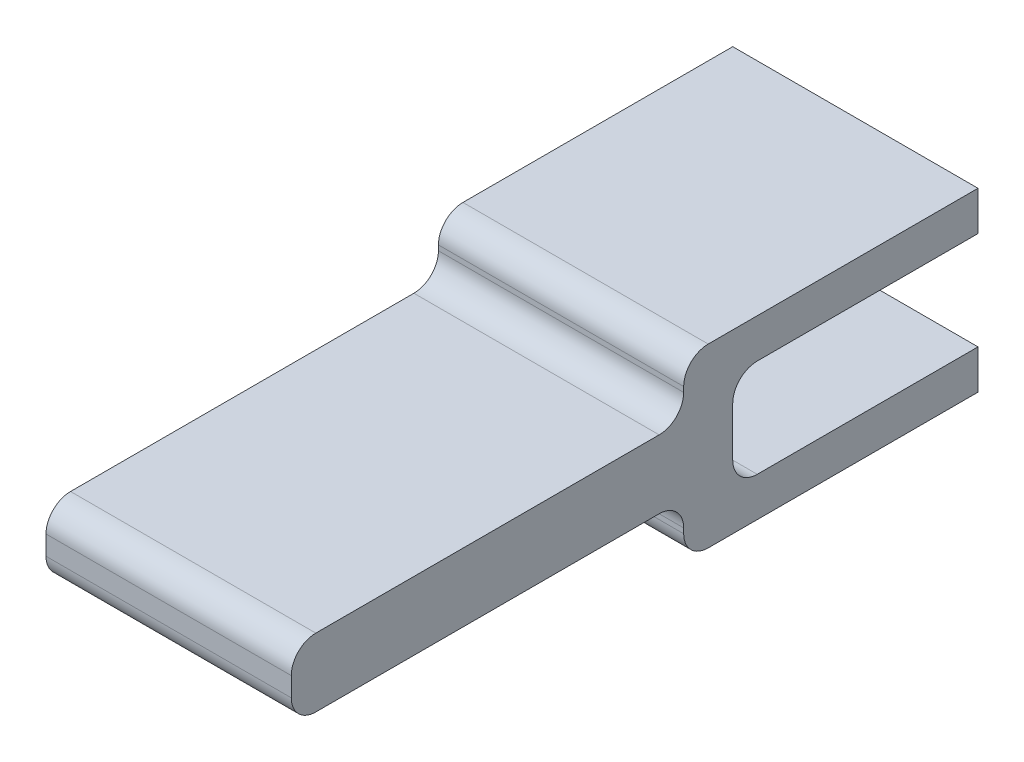
SolidWorks part; units mm, degrees
ref_plane "Front" through (0, 0, 0) normal (0, 0, 1) x (1, 0, 0)
ref_plane "Top" through (0, 0, 0) normal (0, 1, 0) x (1, 0, 0)
ref_plane "Right" through (0, 0, 0) normal (1, 0, 0) x (0, 0, -1)
sketch "Эскиз1" plane through (0, 0, 0) normal (0, 0, 1) x (1, 0, 0)
  line L1 (-2.5, 1) -> (2.5, 1)
  line L2 (-2.5, 1) -> (-2.5, -1)
  line L3 (-2.5, -1) -> (2.5, -1)
  line L4 (2.5, 1) -> (2.5, -1)
  line L5 (-2.5, 1) -> (2.5, -1) construction
  line L6 (-2.5, -1) -> (2.5, 1) construction
  point P0 (0, 0)
  dimension "D1" = 5
  dimension "D2" = 2
extrude "Вытянуть-Тонкостенный1" add sketch "Эскиз1" along normal blind 5 thin thin type one direction wall 0.8
sketch "Эскиз2" plane through (0, 0, 5) normal (0, 0, 1) x (1, 0, 0)
  line L0 (-3.3, -1.8) -> (3.3, -1.8) construction
  line L1 (-3.3, 1.8) -> (-2.5, 1.8)
  line L2 (-3.3, 1.8) -> (-3.3, -1.8)
  line L3 (-3.3, -1.8) -> (-2.5, -1.8)
  line L4 (-2.5, 1.8) -> (-2.5, -1.8)
  line L6 (3.3, 1.8) -> (2.5, 1.8)
  line L7 (3.3, 1.8) -> (3.3, -1.8)
  line L8 (3.3, -1.8) -> (2.5, -1.8)
  line L9 (2.5, 1.8) -> (2.5, -1.8)
extrude "Вырез-Вытянуть2" cut sketch "Эскиз2" against normal up to next
sketch "Эскиз3" plane through (0, 0, 5) normal (0, 0, 1) x (1, 0, 0)
  line L1 (-2.5, 1.8) -> (2.5, 1.8)
  line L2 (-2.5, 1.8) -> (-2.5, -1.8)
  line L3 (-2.5, -1.8) -> (2.5, -1.8)
  line L4 (2.5, 1.8) -> (2.5, -1.8)
extrude "Бобышка-Вытянуть1" add sketch "Эскиз3" along normal blind 1
sketch "Эскиз4" plane through (0, 0, 6) normal (0, 0, 1) x (1, 0, 0)
  line L0 (2.5, -1.8) -> (2.5, 1.8) construction
  line L1 (-2.5, 0.6965) -> (2.5, 0.6965)
  line L2 (-2.5, 0.6965) -> (-2.5, -0.6965)
  line L3 (-2.5, -0.6965) -> (2.5, -0.6965)
  line L4 (2.5, 0.6965) -> (2.5, -0.6965)
  line L5 (-2.5, 0.6965) -> (2.5, -0.6965) construction
  line L6 (-2.5, -0.6965) -> (2.5, 0.6965) construction
  point P0 (0, 0)
extrude "Бобышка-Вытянуть2" add sketch "Эскиз4" along normal blind 8
fillet "Скругление1" radius 0.5 8 edges at (0, 0.6965, 14) (0, -0.6965, 14) (0, -1.8, 6) (0, 1.8, 6) (0, 1, 5) (0, -1, 5) (0, -0.6965, 6) (0, 0.6965, 6)
